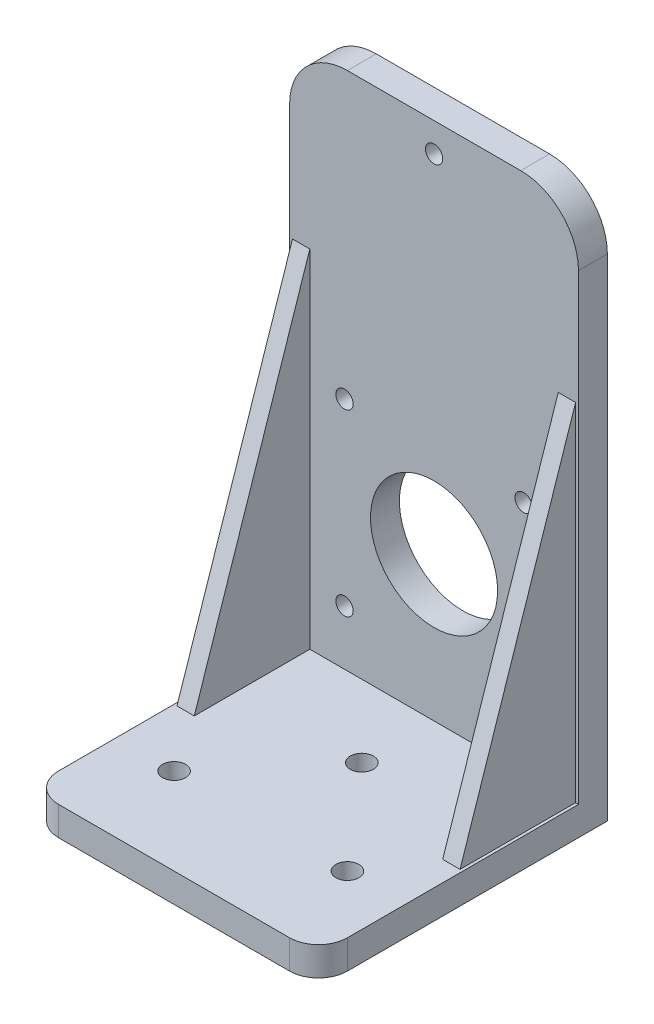
SolidWorks part; units mm, degrees
ref_plane "Plan de face" through (0, 0, 0) normal (0, 0, 1) x (1, 0, 0)
ref_plane "Plan de dessus" through (0, 0, 0) normal (0, 1, 0) x (1, 0, 0)
ref_plane "Plan de droite" through (0, 0, 0) normal (1, 0, 0) x (0, 0, -1)
sketch "Esquisse1" plane through (0, 0, 0) normal (0, 0, 1) x (1, 0, 0)
  line L1 (-20, 25) -> (20, 25)
  line L2 (-25, 20) -> (-25, -25)
  line L3 (-25, -25) -> (25, -25)
  line L4 (25, 20) -> (25, -25)
  line L5 (-25, 25) -> (25, -25) construction
  line L6 (-25, -25) -> (25, 25) construction
  circle A0 centre (0, 0) radius 11
  arc A1 (20, 25) -> (25, 20) centre (20, 20) cw
  arc A2 (-20, 25) -> (-25, 20) centre (-20, 20) ccw
  point P0 (0, 0)
  dimension "D3" = 22
  dimension "D4" = 5
  dimension "50" = 50
  dimension "D2" = 50
extrude "Boss.-Extru.2" add sketch "Esquisse1" along normal blind 5
sketch "Esquisse3" plane through (0, -25, 0) normal (0, -1, 0) x (1, 0, 0)
  line L4 (-25, 0) -> (25, 0)
  line L5 (25, 0) -> (25, 5)
  line L6 (25, 5) -> (-25, 5)
  line L7 (-25, 5) -> (-25, 0)
  line L8 (-25, 0) -> (25, 0)
  line L9 (25, 0) -> (25, 5)
  line L10 (25, 5) -> (-25, 5)
  line L11 (-25, 5) -> (-25, 0)
  dimension "D1" = 0
extrude "Boss.-Extru.4" add sketch "Esquisse3" along normal blind 5
sketch "Esquisse2" plane through (0, 0, 5) normal (0, 0, 1) x (1, 0, 0)
  line L0 (-25, -25) -> (25, -25)
  line L4 (25, -30) -> (25, 20)
  line L5 (20, 25) -> (-20, 25)
  line L6 (-25, 20) -> (-25, -30)
  line L7 (-25, -30) -> (25, -30)
  line L8 (25, -30) -> (25, -25)
  line L10 (-25, -25) -> (-25, -30)
  line L13 (-25, -30) -> (25, -30)
  arc A2 (25, 20) -> (20, 25) centre (20, 20) ccw
  arc A3 (-20, 25) -> (-25, 20) centre (-20, 20) ccw
  dimension "D2" = 5
  dimension "D1" = 0
extrude "Boss.-Extru.3" add sketch "Esquisse2" along normal blind 45
sketch "Esquisse4" plane through (0, 0, 5) normal (0, 0, 1) x (1, 0, 0)
  circle A0 centre (-15.5, 15.5) radius 1.5
  circle A1 centre (15.5, 15.5) radius 1.5
  circle A2 centre (15.5, -15.5) radius 1.5
  circle A3 centre (-15.5, -15.5) radius 1.5
extrude "Enlèv. mat.-Extru.1" cut sketch "Esquisse4" against normal through all
fillet "Congé1" radius 5 2 edges at (-25, -27.5, 50) (25, -27.5, 50)
sketch "Esquisse5" plane through (0, 0, 0) normal (0, 0, -1) x (-1, 0, 0)
  line L3 (0, 101.8868) -> (0, 0) construction
  line L5 (-25, 20) -> (-25, 55)
  line L7 (-15, 65) -> (15, 65)
  line L8 (25, 55) -> (25, 20)
  line L9 (25, 20) -> (25, -30) construction
  circle A0 centre (0, 60) radius 1.5
  arc A2 (25, 20) -> (20, 25) centre (20, 20) ccw construction
  arc A3 (-20, 25) -> (-25, 20) centre (-20, 20) ccw construction
  arc A5 (15, 65) -> (25, 55) centre (15, 55) cw
  arc A6 (-25, 55) -> (-15, 65) centre (-15, 55) cw
  point P14 (0, 68.4056)
  point P16 (0, 0)
  dimension "D2" = 3
  dimension "D4" = 10
  dimension "D1" = 60
  dimension "D3" = 5
extrude "Boss.-Extru.5" add sketch "Esquisse5" against normal blind 5
sketch "Esquisse7" plane through (-25, 0, 0) normal (-1, 0, 0) x (0, 0, 1)
  line L0 (25, -25) -> (5, 35)
  line L1 (45, -25) -> (5, -25) construction
  line L3 (5, 35) -> (5, -25)
  line L4 (5, -25) -> (25, -25)
  line L5 (5, 55) -> (5, -25) construction
  point P4 (5, 38.1314)
  dimension "D1" = 20
  dimension "D2" = 60
extrude "Boss.-Extru.6" add sketch "Esquisse7" against normal blind 3 from offset 0.5 offset against normal yes
mirror "Symétrie1" about plane through (0, 0, 0) normal (1, 0, 0) of "Boss.-Extru.6"
sketch "Esquisse9" plane through (0, -25, 0) normal (0, 1, 0) x (1, 0, 0)
  line L0 (-25, -35) -> (25, -35) construction
  line L1 (-25, -45) -> (-25, -5) construction
  line L2 (25, -45) -> (25, -5) construction
  line L3 (20, -50) -> (-20, -50) construction
  line L4 (0, 0) -> (0, -35) construction
  circle A0 centre (-15, -35) radius 2
  circle A1 centre (15, -35) radius 2
  circle A2 centre (0, -17.5) radius 2
  dimension "D2" = 4
  dimension "D4" = 4
  dimension "D1" = 15
  dimension "D3" = 10
extrude "Enlèv. mat.-Extru.3" cut sketch "Esquisse9" against normal through all
